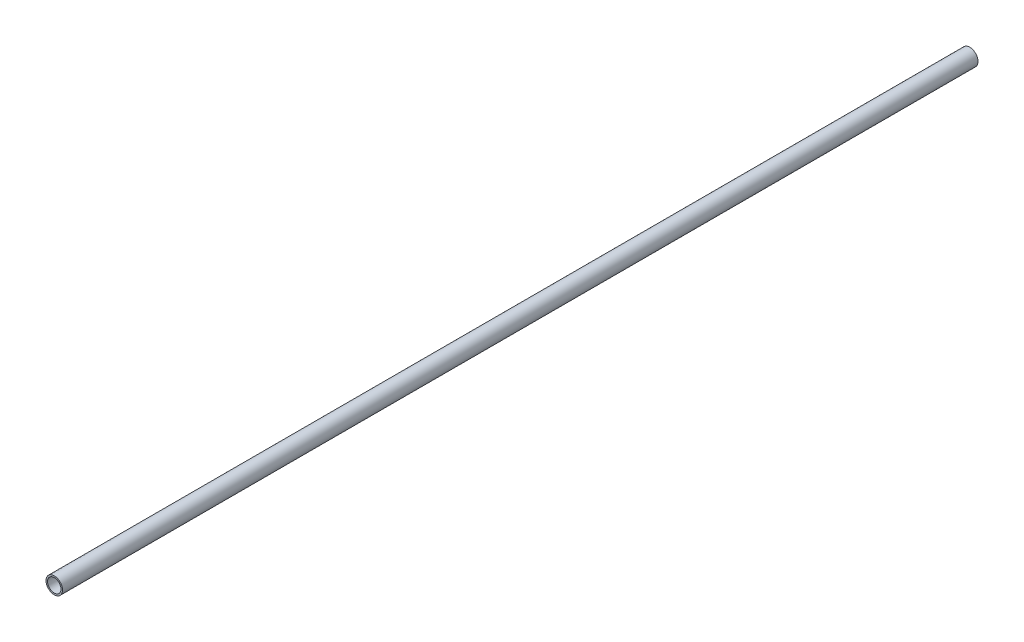
SolidWorks part; units mm, degrees
material "1.0254 (P235TR1)"
ref_plane "Vorne" through (0, 0, 0) normal (0, 0, 1) x (1, 0, 0)
ref_plane "Oben" through (0, 0, 0) normal (0, 1, 0) x (1, 0, 0)
ref_plane "Rechts" through (0, 0, 0) normal (1, 0, 0) x (0, 0, -1)
sketch "Skizze1" plane through (0, 0, 0) normal (0, 0, 1) x (1, 0, 0)
  circle A0 centre (0, 0) radius 17.35
  circle A1 centre (0, 0) radius 21.35
  dimension "D1" = 42.7
  dimension "D2" = 4
extrude "Linear austragen1" add sketch "Skizze1" along normal mid plane 2370
cosmetic thread "Gewindedarstellung6" parameters "D1"=25, "D2"=38.953
cosmetic thread "Gewindedarstellung7" parameters "D1"=25, "D2"=38.953
